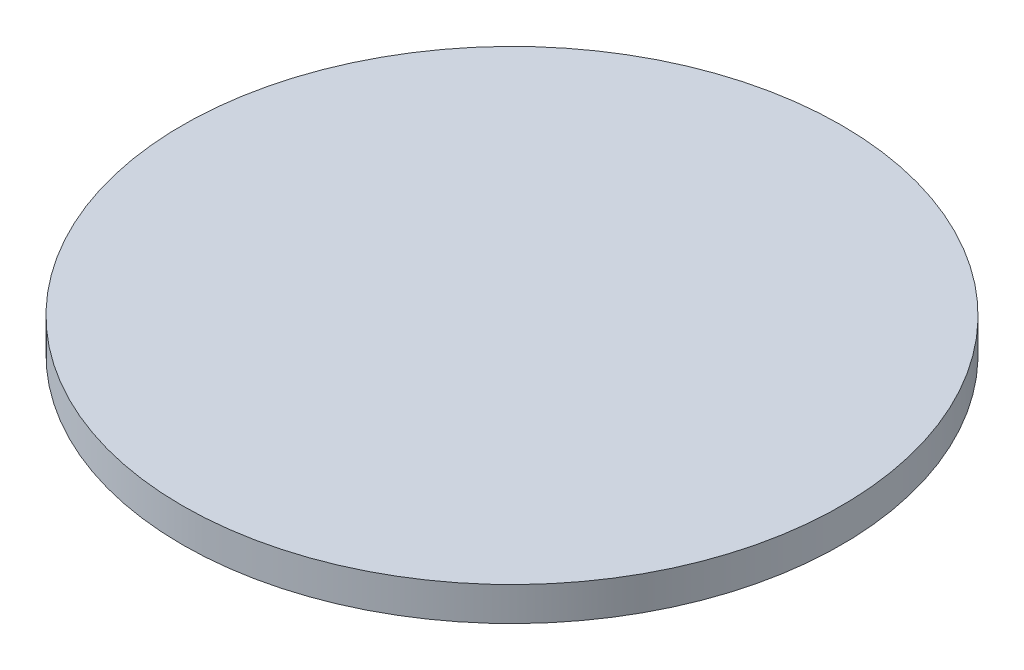
SolidWorks part; units mm, degrees
ref_plane "Front Plane" through (0, 0, 0) normal (0, 0, 1) x (1, 0, 0)
ref_plane "Top Plane" through (0, 0, 0) normal (0, 1, 0) x (1, 0, 0)
ref_plane "Right Plane" through (0, 0, 0) normal (1, 0, 0) x (0, 0, -1)
sketch "Sketch1" plane through (0, 0, 0) normal (0, 1, 0) x (1, 0, 0)
  circle A0 centre (0, 0) radius 49.53
  dimension "D1" = 99.06
extrude "Boss-Extrude1" add sketch "Sketch1" along normal blind 5.08
